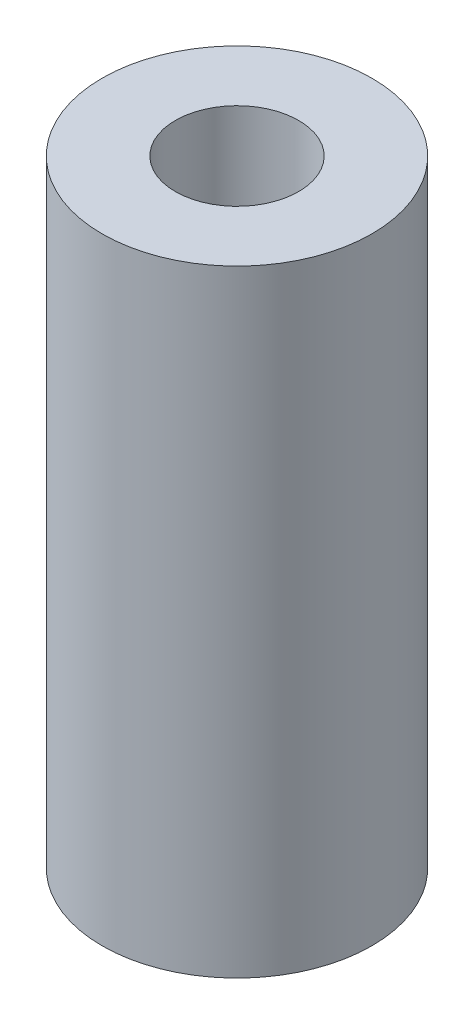
SolidWorks part; units mm, degrees
material "Brass"
ref_plane "Front Plane" through (0, 0, 0) normal (0, 0, 1) x (1, 0, 0)
ref_plane "Top Plane" through (0, 0, 0) normal (0, 1, 0) x (1, 0, 0)
ref_plane "Right Plane" through (0, 0, 0) normal (1, 0, 0) x (0, 0, -1)
sketch "Sketch1" plane through (0, 0, 0) normal (0, 0, 1) x (1, 0, 0)
  line L0 (0, 0) -> (0, 22.592) construction
  line L2 (0, 0) -> (-1.75, 0)
  line L3 (0, 0) -> (0, 8)
  line L4 (0, 8) -> (-1.75, 8)
  line L5 (-1.75, 0) -> (-1.75, 8)
  dimension "D1" = 8
  dimension "D2" = 3.5
revolve "Revolve1" add sketch "Sketch1" angle 360 about L0
hole_wizard "M2x0.4 Tapped Hole1" positions "Sketch4" profile "Sketch3" tap size "M2x0.4" standard "ANSI Metric" end condition up to next
sketch "Sketch4" plane through (0, 8, 0) normal (0, 1, 0) x (-1, 0, 0)
  point P0 (0, 0)
sketch "Sketch3" plane through (0, 8, 0) normal (1, 0, 0) x (0, 0, 1)
  line L0 (0, 0) -> (0, 8)
  line L1 (0, 8) -> (0.8, 8)
  line L2 (0.8, 8) -> (0.8, 0)
  line L5 (0.8, 0) -> (0, 0)
  line L11 (0, -6.35) -> (0, 107.95) construction
  dimension "Thru Tap Drill Dia." = 1.6
  dimension "Thru Tap Drill Depth" = 8
cosmetic thread "Hole Thread1" parameters "D2"=2
